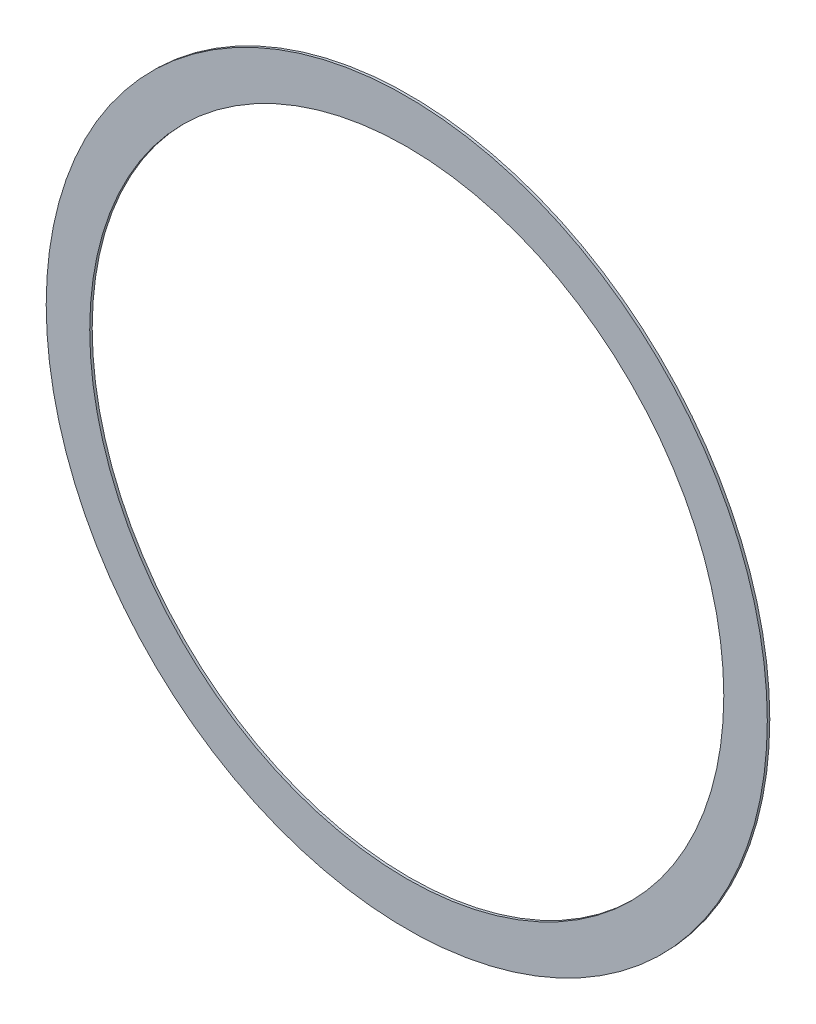
SolidWorks part; units mm, degrees
ref_plane "Front Plane" through (0, 0, 0) normal (0, 0, 1) x (1, 0, 0)
ref_plane "Top Plane" through (0, 0, 0) normal (0, 1, 0) x (1, 0, 0)
ref_plane "Right Plane" through (0, 0, 0) normal (1, 0, 0) x (0, 0, -1)
sketch "Sketch1" plane through (0, 0, 0) normal (0, 0, 1) x (1, 0, 0)
  circle A0 centre (0, 0) radius 12.75
  circle A1 centre (0, 0) radius 14.5
  dimension "D1" = 29
  dimension "D2" = 25.5
extrude "Boss-Extrude1" add sketch "Sketch1" along normal blind 0.1
